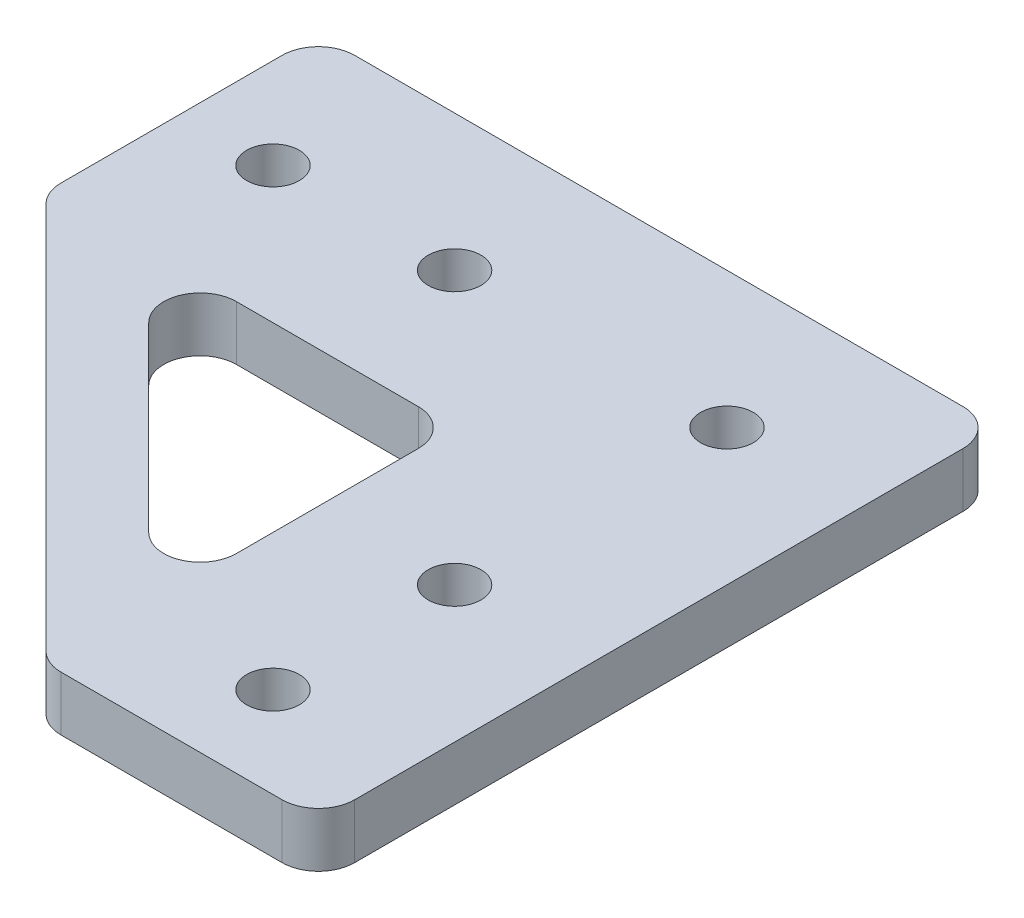
SolidWorks part; units mm, degrees
material "Thornel Mat VMA"
ref_plane "前视基准面" through (0, 0, 0) normal (0, 0, 1) x (1, 0, 0)
ref_plane "上视基准面" through (0, 0, 0) normal (0, 1, 0) x (1, 0, 0)
ref_plane "右视基准面" through (0, 0, 0) normal (1, 0, 0) x (0, 0, -1)
other "Configuration Table"
sketch "草图1" plane through (0, 0, 0) normal (0, 1, 0) x (1, 0, 0)
  line L0 (-37.5, -7.5) -> (0, -7.5) construction
  line L1 (0, 0) -> (-37.5, 0)
  line L2 (0, 0) -> (0, -37.5)
  line L3 (0, -37.5) -> (-15, -37.5)
  line L4 (-37.5, 0) -> (-37.5, -15)
  line L7 (-37.5, -15) -> (-15, -15)
  line L8 (-15, -37.5) -> (-15, -15)
  line L9 (-7.5, -37.5) -> (-7.5, 0) construction
  circle A0 centre (-7.5, -7.5) radius 1.45
  circle A1 centre (-22.5, -7.5) radius 1.45
  circle A2 centre (-32.5, -7.5) radius 1.45
  circle A3 centre (-7.5, -22.5) radius 1.45
  circle A4 centre (-7.5, -32.5) radius 1.45
  dimension "D3" = 2.9
  dimension "D4" = 2.9
  dimension "D5" = 2.9
  dimension "D6" = 7.5
  dimension "D7" = 10
  dimension "D9" = 2.9
  dimension "D10" = 2.9
  dimension "D12" = 10
  dimension "D1" = 15
  dimension "D2" = 15
  dimension "D8" = 37.5
  dimension "D11" = 7.5
  dimension "D13" = 37.5
extrude "凸台-拉伸1" add sketch "草图1" along normal blind 3
sketch "草图2" plane through (0, 3, 0) normal (0, 1, 0) x (1, 0, 0)
  line L0 (-37.5, -15) -> (-15, -37.5)
  line L1 (-15, -37.5) -> (-15, -31.8431)
  line L2 (-15, -15) -> (-15, -37.5) construction
  line L3 (-15, -31.8431) -> (-31.8431, -15)
  line L4 (-37.5, -15) -> (-15, -15) construction
  line L5 (-31.8431, -15) -> (-37.5, -15)
  dimension "D1" = 4
extrude "凸台-拉伸2" add sketch "草图2" against normal blind 3
fillet "圆角1" radius 2 8 edges at (-15, 1.5, 37.5) (-37.5, 1.5, 15) (-37.5, 1.5, 0) (0, 1.5, 0) (0, 1.5, 37.5) (-15, 1.5, 31.8431) (-31.8431, 1.5, 15) (-15, 1.5, 15)
